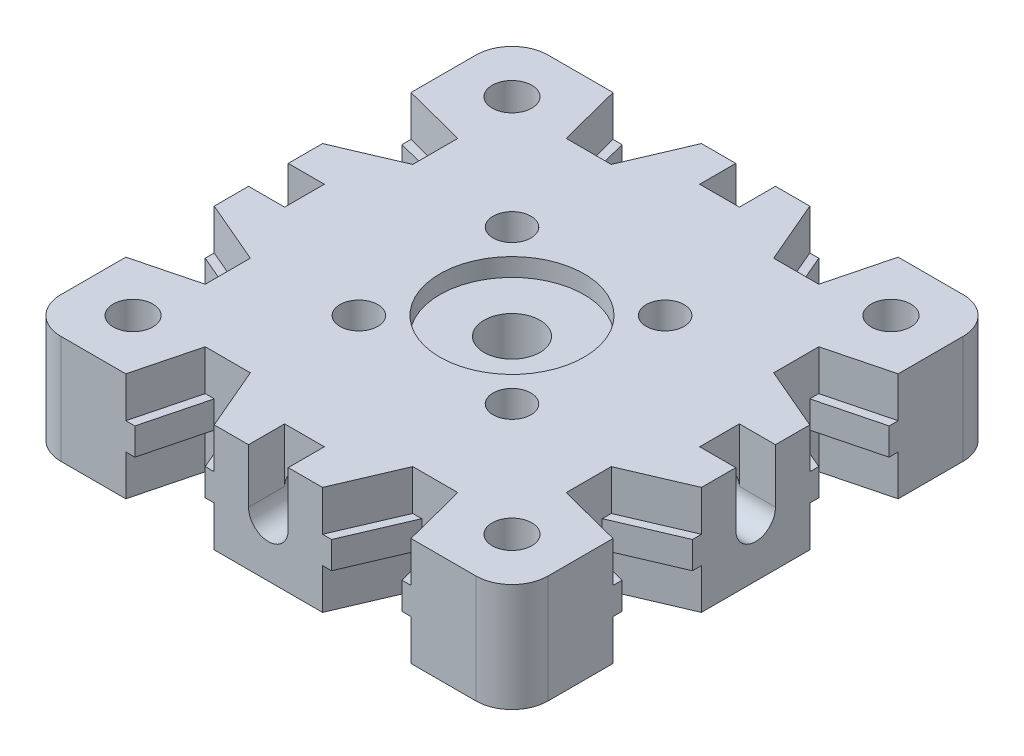
SolidWorks part; units mm, degrees
material "ABS"
ref_plane "正面" through (0, 0, 0) normal (0, 0, 1) x (1, 0, 0)
ref_plane "平面" through (0, 0, 0) normal (0, 1, 0) x (1, 0, 0)
ref_plane "右側面" through (0, 0, 0) normal (1, 0, 0) x (0, 0, -1)
sketch "ｽｹｯﾁ3" plane through (0, 0, 0) normal (0, 1, 0) x (1, 0, 0)
  line L1 (-13.5, 13.5) -> (13.5, 13.5)
  line L2 (-13.5, 13.5) -> (-13.5, -13.5)
  line L3 (-13.5, -13.5) -> (13.5, -13.5)
  line L4 (13.5, 13.5) -> (13.5, -13.5)
  line L5 (-13.5, 13.5) -> (13.5, -13.5) construction
  line L6 (-13.5, -13.5) -> (13.5, 13.5) construction
  point P0 (0, 0)
  dimension "D1" = 27
extrude "ﾎﾞｽ - 押し出し1" add sketch "ｽｹｯﾁ3" along normal mid plane 6
fillet "ﾌｨﾚｯﾄ1" radius 2 4 edges at (-13.5, 0, -13.5) (13.5, 0, -13.5) (-13.5, 0, 13.5) (13.5, 0, 13.5)
sketch "ｽｹｯﾁ4" plane through (0, 3, 0) normal (0, 1, 0) x (1, 0, 0)
  line L1 (-10.5, 10.5) -> (10.5, 10.5) construction
  line L2 (-10.5, 10.5) -> (-10.5, -10.5) construction
  line L3 (-10.5, -10.5) -> (10.5, -10.5) construction
  line L4 (10.5, 10.5) -> (10.5, -10.5) construction
  line L5 (-10.5, 10.5) -> (10.5, -10.5) construction
  line L6 (-10.5, -10.5) -> (10.5, 10.5) construction
  circle A0 centre (-10.5, 10.5) radius 1.1
  circle A1 centre (10.5, 10.5) radius 1.1
  circle A2 centre (-10.5, -10.5) radius 1.1
  circle A3 centre (10.5, -10.5) radius 1.1
  point P0 (0, 0)
  dimension "D6" = 2.2
  dimension "D1" = 21
  dimension "D2" = 21
extrude "ｶｯﾄ - 押し出し1" cut sketch "ｽｹｯﾁ4" against normal blind 6
sketch "ｽｹｯﾁ5" plane through (0, 3, 0) normal (0, 1, 0) x (1, 0, 0)
  circle A0 centre (0, 0) radius 1.55
  dimension "D1" = 3.1
extrude "ｶｯﾄ - 押し出し2" cut sketch "ｽｹｯﾁ5" against normal blind 6
sketch "ｽｹｯﾁ6" plane through (0, 3, 0) normal (0, 1, 0) x (1, 0, 0)
  line L0 (4.2426, 4.2426) -> (0, 0)
  line L1 (0, 0) -> (3.3762, 0)
  circle A0 centre (4.2426, 4.2426) radius 1.05
  dimension "D1" = 2.1
  dimension "D2" = 45
  dimension "D3" = 6
extrude "ｶｯﾄ - 押し出し3" cut sketch "ｽｹｯﾁ6" against normal blind 6
pattern_circular "円形ﾊﾟﾀｰﾝ1" count 4 over 360 about axis through (0, 0, 0) along (0, 1, 0) of "ｶｯﾄ - 押し出し3"
sketch "ｽｹｯﾁ7" plane through (0, 3, 0) normal (0, 1, 0) x (1, 0, 0)
  circle A0 centre (0, 0) radius 4
  dimension "D1" = 8
extrude "ｶｯﾄ - 押し出し4" cut sketch "ｽｹｯﾁ7" against normal blind 1
sketch "ｽｹｯﾁ11" plane through (0, 3, 0) normal (0, 1, 0) x (1, 0, 0)
  line L0 (3, 13.5) -> (4.5, 10)
  line L1 (11.5, 13.5) -> (-11.5, 13.5) construction
  line L2 (4.5, 10) -> (7, 10)
  line L3 (7, 10) -> (7.9, 13.5)
  dimension "D1" = 3.5
  dimension "D2" = 2.5
  dimension "D3" = 7
  dimension "D4" = 3
  dimension "D5" = 7.9
extrude "ｶｯﾄ - 押し出し8" cut sketch "ｽｹｯﾁ11" against normal through all and the other way through all
mirror "ﾐﾗｰ1" about plane through (0, 0, 0) normal (1, 0, 0) of "ｶｯﾄ - 押し出し8"
pattern_circular "円形ﾊﾟﾀｰﾝ2" count 4 over 360 about axis through (0, 0, 0) along (0, 1, 0) of "ｶｯﾄ - 押し出し8", "ﾐﾗｰ1"
sketch "ｽｹｯﾁ12" plane through (0, 0, 13.5) normal (0, 0, 1) x (1, 0, 0)
  circle A0 centre (0, 0) radius 1.1
  dimension "D1" = 2.2
extrude "ｶｯﾄ - 押し出し9" cut sketch "ｽｹｯﾁ12" against normal blind 8
pattern_circular "円形ﾊﾟﾀｰﾝ3" count 4 over 360 about axis through (0, 0, 0) along (0, 1, 0) of "ｶｯﾄ - 押し出し9"
sketch "ｽｹｯﾁ13" plane through (0, 0, 0) normal (0, 1, 0) x (1, 0, 0)
  line L0 (7.9, 13.5) -> (7, 10)
  line L1 (7, 10) -> (6.5, 10)
  line L2 (7, 10) -> (4.5, 10) construction
  line L3 (6.5, 10) -> (7.4, 13.5)
  line L4 (7.4, 13.5) -> (7.9, 13.5)
  line L5 (3, 13.5) -> (3.5, 13.5)
  line L6 (3.5, 13.5) -> (5, 10)
  line L7 (5, 10) -> (4.5, 10)
  line L8 (4.5, 10) -> (3, 13.5)
  dimension "D1" = 0.5
  dimension "D2" = 0.5
extrude "ﾎﾞｽ - 押し出し2" add sketch "ｽｹｯﾁ13" along normal mid plane 1.5
mirror "ﾐﾗｰ2" about plane through (0, 0, 0) normal (1, 0, 0) of "ﾎﾞｽ - 押し出し2"
pattern_circular "円形ﾊﾟﾀｰﾝ4" count 4 over 360 about axis through (0, 0, 0) along (0, 1, 0) of "ﾎﾞｽ - 押し出し2", "ﾐﾗｰ2"
ref_plane "平面1" through (0, 0, -10.5) normal (0, 0, -1) x (-1, 0, 0)
sketch "ｽｹｯﾁ18" plane through (0, 3, 0) normal (0, 1, 0) x (1, 0, 0)
  line L0 (0, 0) -> (6, 0)
  line L1 (0, 0) -> (0, 6)
  dimension "D1" = 6
sketch "ｽｹｯﾁ19" plane through (0, 0, 0) normal (0, 0, 1) x (1, 0, 0)
  line L0 (0, 3) -> (0, 9)
  line L1 (0, 3) -> (6, 3) construction
sketch "ｽｹｯﾁ22" plane through (0, 0, 13.5) normal (0, 0, 1) x (1, 0, 0)
  line L0 (0, 3) -> (6, 3) construction
  line L1 (-1.1, 0) -> (1.1, 0)
  line L2 (-1.1, 0) -> (-1.1, 3)
  line L3 (-1.1, 3) -> (1.1, 3)
  line L4 (1.1, 0) -> (1.1, 3)
  line L5 (-1.1, 0) -> (1.1, 3) construction
  line L6 (-1.1, 3) -> (1.1, 0) construction
  circle A0 centre (0, 0) radius 1.1 construction
  circle A1 centre (0, 0) radius 1.1 construction
  point P4 (0, 1.5)
extrude "ｶｯﾄ - 押し出し15" cut sketch "ｽｹｯﾁ22" against normal blind 2
pattern_circular "円形ﾊﾟﾀｰﾝ11" count 4 over 360 about axis through (0, 0, 0) along (0, 1, 0) of "ｶｯﾄ - 押し出し15"
sketch "ｽｹｯﾁ27" plane through (0, -3, 0) normal (0, -1, 0) x (1, 0, 0)
  line L0 (0, -6) -> (0, 0)
  line L1 (0, 0) -> (-6, 0)
